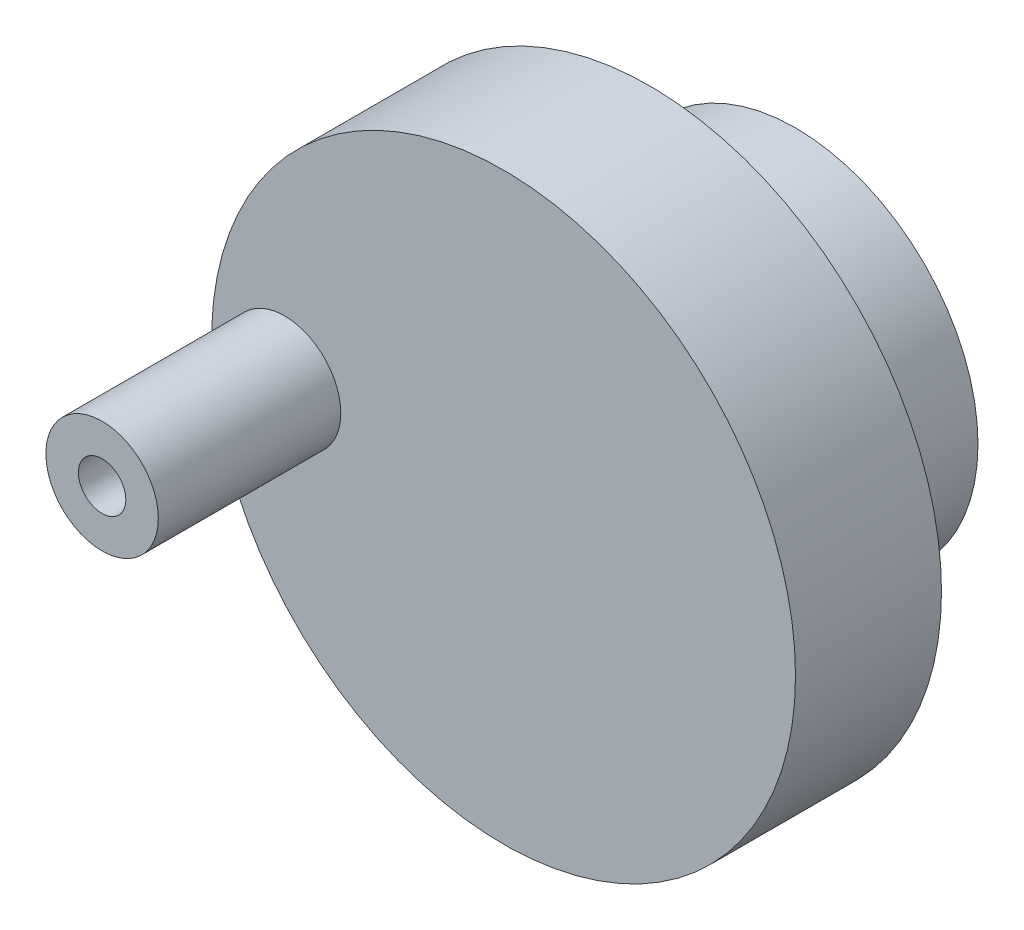
SolidWorks part; units mm, degrees
ref_plane "Front Plane" through (0, 0, 0) normal (0, 0, 1) x (1, 0, 0)
ref_plane "Top Plane" through (0, 0, 0) normal (0, 1, 0) x (1, 0, 0)
ref_plane "Right Plane" through (0, 0, 0) normal (1, 0, 0) x (0, 0, -1)
sketch "Sketch1" plane through (0, 0, 0) normal (0, 0, 1) x (1, 0, 0)
  circle A0 centre (0, 0) radius 20
  dimension "D1" = 40
extrude "Boss-Extrude1" add sketch "Sketch1" along normal blind 10
sketch "Sketch2" plane through (0, 0, 10) normal (0, 0, 1) x (1, 0, 0)
  circle A0 centre (-15, 0) radius 3.85
  dimension "D1" = 7.7
  dimension "D2" = 15
extrude "Boss-Extrude2" add sketch "Sketch2" along normal blind 12.5
sketch "Sketch3" plane through (0, 0, 0) normal (0, 0, -1) x (-1, 0, 0)
  line L1 (3.4641, 6) -> (-3.4641, 6)
  line L2 (-3.4641, 6) -> (-6.9282, 0)
  line L3 (-6.9282, 0) -> (-3.4641, -6)
  line L4 (-3.4641, -6) -> (3.4641, -6)
  line L5 (3.4641, -6) -> (6.9282, 0)
  line L6 (6.9282, 0) -> (3.4641, 6)
  circle A2 centre (0, 0) radius 6 construction
  circle A3 centre (0, 0) radius 12.5
  dimension "D1" = 12
  dimension "D2" = 25
extrude "Boss-Extrude3" add sketch "Sketch3" along normal blind 10
sketch "Sketch4" plane through (0, 0, -10) normal (0, 0, -1) x (-1, 0, 0)
  line L0 (0, 0) -> (-12.5, 0) construction
  circle A0 centre (0, 0) radius 12.5 construction
sketch "Sketch5" plane through (0, 0, 22.5) normal (0, 0, 1) x (1, 0, 0)
  circle A0 centre (-15, 0) radius 1.5
  circle A1 centre (-15, 0) radius 3.85 construction
  dimension "D1" = 3
extrude "Cut-Extrude1" cut sketch "Sketch5" against normal blind 16.5
sketch "Sketch6" plane through (0, 0, 22.5) normal (0, 0, 1) x (1, 0, 0)
  circle A0 centre (-15, 0) radius 1.625
  circle A1 centre (-15, 0) radius 3.85 construction
  dimension "D1" = 3.25
extrude "Cut-Extrude2" cut sketch "Sketch6" against normal blind 5.2
fillet "Fillet1" radius 5 1 edges at (12.5, 0, 0)
